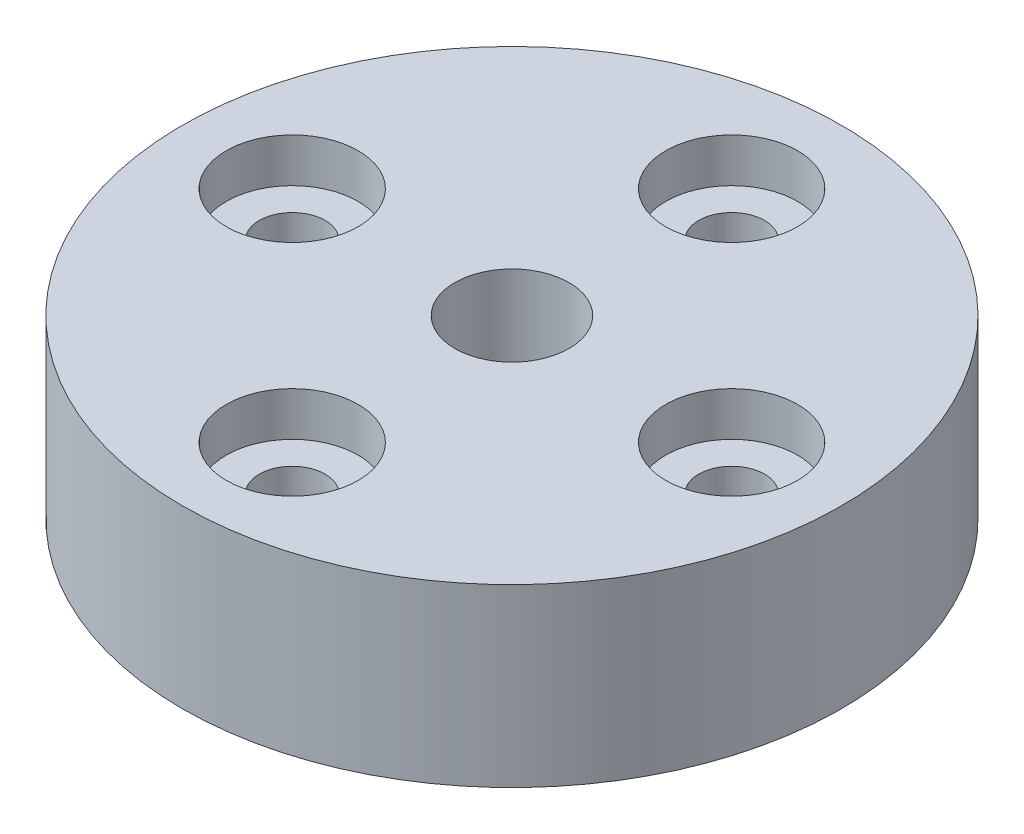
SolidWorks part; units mm, degrees
ref_plane "前视基准面" through (0, 0, 0) normal (0, 0, 1) x (1, 0, 0)
ref_plane "上视基准面" through (0, 0, 0) normal (0, 1, 0) x (1, 0, 0)
ref_plane "右视基准面" through (0, 0, 0) normal (1, 0, 0) x (0, 0, -1)
other "Configuration Table"
sketch "Sketch1" plane through (0, 0, 0) normal (0, 1, 0) x (1, 0, 0)
  circle A0 centre (0, 0) radius 15
  circle A1 centre (0, 0) radius 10
  circle A2 centre (0, 10) radius 1.5
  circle A3 centre (10, 0) radius 1.5
  circle A4 centre (0, -10) radius 1.5
  circle A5 centre (-10, 0) radius 1.5
  point P15 (0, 0)
  dimension "D1" = 30
  dimension "D2" = 20
  dimension "D3" = 3
  dimension "D4" = 4
extrude "Boss-Extrude1" add sketch "Sketch1" along normal blind 8 contours A0 A5 A1 A2 A3 A4 | A5 A1 A4 A3 A2
sketch "Sketch2" plane through (0, 8, 0) normal (0, 1, 0) x (1, 0, 0)
  circle A0 centre (0, 0) radius 2.6
  dimension "D1" = 5.2
extrude "Cut-Extrude1" cut sketch "Sketch2" against normal through all
sketch "Sketch3" plane through (0, 8, 0) normal (0, 1, 0) x (1, 0, 0)
  circle A0 centre (0, 10) radius 3
  circle A1 centre (10, 0) radius 3
  circle A2 centre (0, -10) radius 3
  circle A3 centre (-10, 0) radius 3
  point P12 (0, 0)
  circle M2 centre (-10, 0) radius 1.5
  circle M4 centre (10, 0) radius 1.5
  circle M5 centre (0, -10) radius 1.5
  dimension "D1" = 6
  dimension "D2" = 4
extrude "Cut-Extrude2" cut sketch "Sketch3" against normal blind 2 contours A3 M2 | A2 M5 | A1 M4 | A0
sketch "Sketch4" plane through (0, 0, 0) normal (0, -1, 0) x (1, 0, 0)
  circle A0 centre (0, 10) radius 3
  circle A1 centre (10, 0) radius 3
  circle A2 centre (0, -10) radius 3
  circle A3 centre (-10, 0) radius 3
  point P12 (0, 0)
  dimension "D1" = 6
  dimension "D2" = 4
extrude "Cut-Extrude3" cut sketch "Sketch4" against normal blind 2
